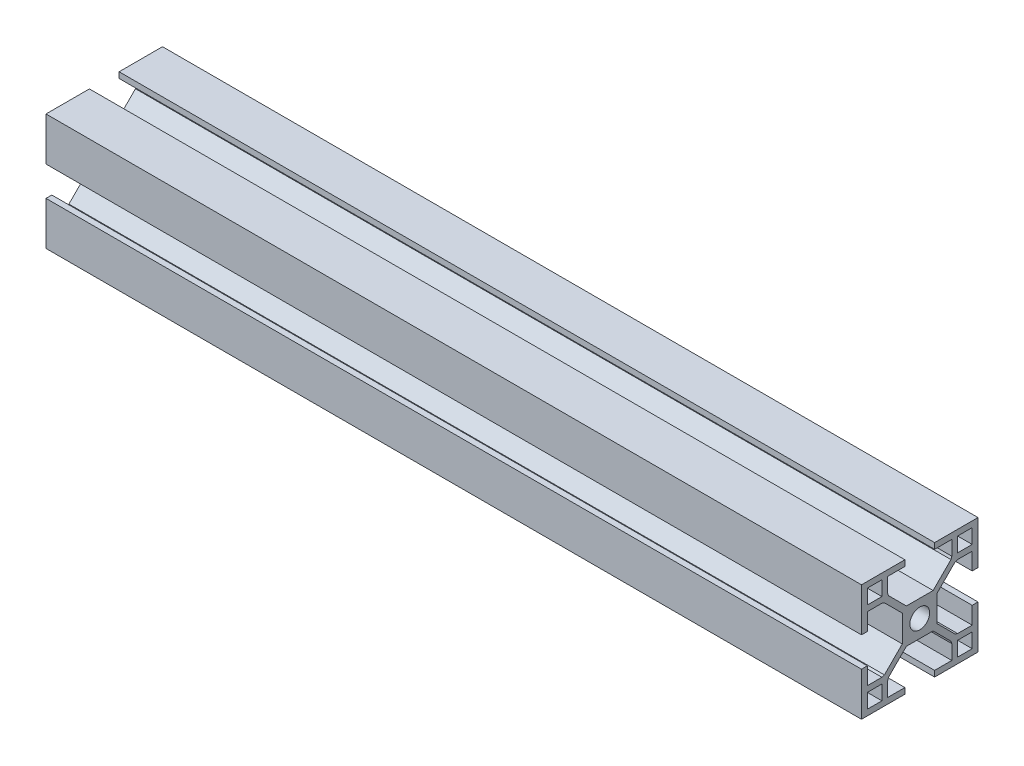
SolidWorks part; units mm, degrees
ref_plane "前视基准面" through (0, 0, 0) normal (0, 0, 1) x (1, 0, 0)
ref_plane "上视基准面" through (0, 0, 0) normal (0, 1, 0) x (1, 0, 0)
ref_plane "右视基准面" through (0, 0, 0) normal (1, 0, 0) x (0, 0, -1)
sketch "草图1" plane through (0, 0, 0) normal (1, 0, 0) x (0, 0, -1)
  line L0 (0, 0) -> (0, 6) construction
  line L5 (0, 6) -> (4.5858, 6)
  line L6 (6, 0) -> (6, -4.5858)
  line L10 (12.133, -10.7188) -> (6, -4.5858)
  line L11 (10.7188, 12.133) -> (4.5858, 6)
  line L12 (20, 20) -> (20, 5.1)
  line L18 (20, -20) -> (5.1, -20)
  line L22 (12.133, -10.7188) -> (13, -11)
  line L23 (18, -13) -> (18, -18)
  line L24 (18, -15.5) -> (18, -13)
  line L28 (18, -13) -> (13, -13)
  line L32 (13, -13) -> (13, -18)
  line L33 (18, -18) -> (13, -18)
  line L34 (11, -13) -> (11, -18)
  line L38 (11, -18) -> (5.1, -18)
  line L42 (10.7188, -12.133) -> (11, -13)
  line L43 (10.7188, -12.133) -> (4.5858, -6)
  line L44 (4.5858, -6) -> (0, -6)
  line L45 (10.7188, 12.133) -> (11, 13)
  line L46 (5.1, -18) -> (5.1, -20)
  line L47 (13, 18) -> (18, 18)
  line L49 (15.5, 18) -> (13, 18)
  line L56 (13, 18) -> (13, 13)
  line L59 (13, 13) -> (18, 13)
  line L60 (18, 18) -> (18, 13)
  line L61 (13, 11) -> (18, 11)
  line L62 (18, 11) -> (18, 5.1)
  line L63 (12.133, 10.7188) -> (13, 11)
  line L64 (12.133, 10.7188) -> (6, 4.5858)
  line L65 (6, 4.5858) -> (6, 0)
  line L66 (18, 5.1) -> (20, 5.1)
  line L67 (11, 18) -> (5.1, 18)
  line L68 (11, 13) -> (11, 18)
  line L69 (5.1, 18) -> (5.1, 20)
  line L70 (20, 20) -> (5.1, 20)
  line L71 (18, -11) -> (18, -5.1)
  line L72 (13, -11) -> (18, -11)
  line L73 (18, -5.1) -> (20, -5.1)
  line L74 (20, -20) -> (20, -5.1)
  line L75 (0, 0) -> (6, 0) construction
  line L76 (0, -6) -> (-4.5858, -6)
  line L77 (-10.7188, -12.133) -> (-4.5858, -6)
  line L78 (-20, -20) -> (-20, -5.1)
  line L79 (-10.7188, -12.133) -> (-11, -13)
  line L80 (-13, -18) -> (-18, -18)
  line L81 (-15.5, -18) -> (-13, -18)
  line L82 (-13, -18) -> (-13, -13)
  line L83 (-13, -13) -> (-18, -13)
  line L84 (-18, -18) -> (-18, -13)
  line L85 (-13, -11) -> (-18, -11)
  line L86 (-18, -11) -> (-18, -5.1)
  line L87 (-12.133, -10.7188) -> (-13, -11)
  line L88 (-12.133, -10.7188) -> (-6, -4.5858)
  line L89 (-6, -4.5858) -> (-6, 0)
  line L90 (-18, -5.1) -> (-20, -5.1)
  line L91 (-11, -18) -> (-5.1, -18)
  line L92 (-11, -13) -> (-11, -18)
  line L93 (-5.1, -18) -> (-5.1, -20)
  line L94 (-20, -20) -> (-5.1, -20)
  line L95 (0, 0) -> (0, -6) construction
  line L96 (-6, 0) -> (-6, 4.5858)
  line L97 (-12.133, 10.7188) -> (-6, 4.5858)
  line L98 (-20, 20) -> (-5.1, 20)
  line L99 (-12.133, 10.7188) -> (-13, 11)
  line L100 (-18, 13) -> (-18, 18)
  line L101 (-18, 15.5) -> (-18, 13)
  line L102 (-18, 13) -> (-13, 13)
  line L103 (-13, 13) -> (-13, 18)
  line L104 (-18, 18) -> (-13, 18)
  line L105 (-11, 13) -> (-11, 18)
  line L106 (-11, 18) -> (-5.1, 18)
  line L107 (-10.7188, 12.133) -> (-11, 13)
  line L108 (-10.7188, 12.133) -> (-4.5858, 6)
  line L109 (-4.5858, 6) -> (0, 6)
  line L110 (-5.1, 18) -> (-5.1, 20)
  line L111 (-18, 11) -> (-18, 5.1)
  line L112 (-13, 11) -> (-18, 11)
  line L113 (-18, 5.1) -> (-20, 5.1)
  line L114 (-20, 20) -> (-20, 5.1)
  line L115 (0, 0) -> (-6, 0) construction
  circle A0 centre (0, 0) radius 3.4
extrude "凸台-拉伸1" add sketch "草图1" along normal blind 280 contours L84 L80 L82 L83 | L33 L23 L28 L32 | L60 L47 L56 L59 | L12 L66 L62 L61 L63 L64 L65 L6 L10 L22 L72 L71 L73 L74 L18 L46 L38 L34 L42 L43 L44 L76 L77 L79 L92 L91 L93 L94 L78 L90 L86 L85 L87 L88 L89 L96 L97 L99 L112 L111 L113 L114 L98 L110 L106 L105 L107 L108 L109 L5 L11 L45 L68 L67 L69 L70 | A0 | L102 L103 L104 L100
